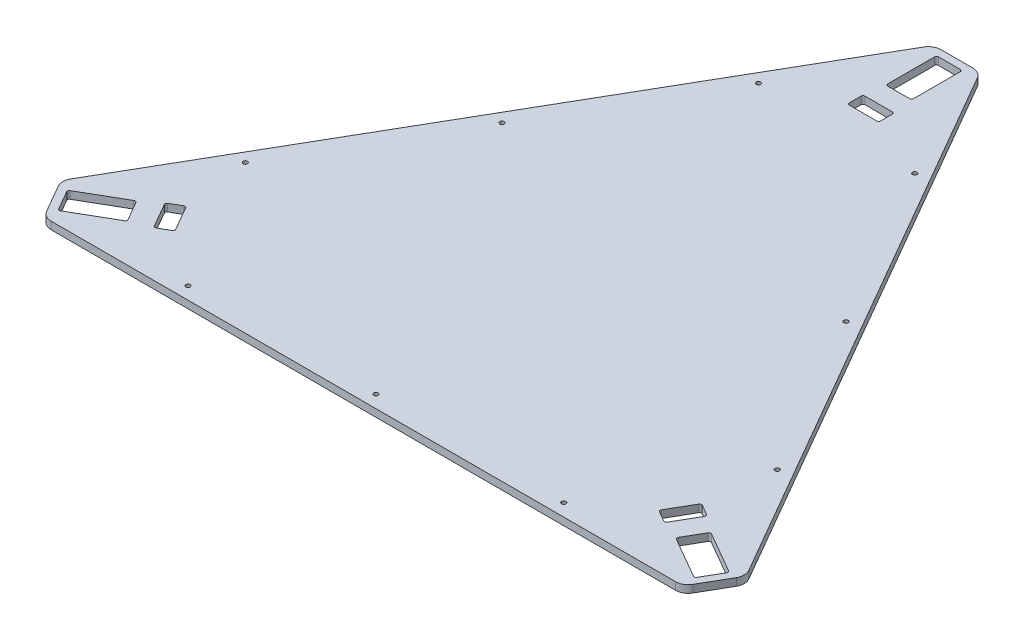
SolidWorks part; units mm, degrees
material "ABS"
ref_plane "Спереди" through (0, 0, 0) normal (0, 0, 1) x (1, 0, 0)
ref_plane "Сверху" through (0, 0, 0) normal (0, 1, 0) x (1, 0, 0)
ref_plane "Справа" through (0, 0, 0) normal (1, 0, 0) x (0, 0, -1)
sketch "Эскиз1" plane through (0, 0, 0) normal (0, 1, 0) x (1, 0, 0)
  line L17 (273.664, -136.638) -> (18.5, 305.319)
  line L18 (18.5, 305.319) -> (-18.5, 305.319)
  line L19 (-18.5, 305.319) -> (-273.664, -136.638)
  line L29 (219.0188, -138.2863) -> (254.0929, -158.5363)
  line L30 (-10.25, 299.319) -> (10.25, 299.319)
  line L31 (-273.664, -136.638) -> (-255.164, -168.681)
  line L32 (-255.164, -168.681) -> (255.164, -168.681)
  line L33 (255.164, -168.681) -> (273.664, -136.638)
  line L34 (-264.414, -152.6595) -> (0, 0) construction
  line L35 (0, 0) -> (146.082, 84.3405) construction
  line L36 (264.414, -152.6595) -> (0, 0) construction
  line L37 (0, 0) -> (-146.082, 84.3405) construction
  line L38 (0, 305.319) -> (0, 0) construction
  line L39 (0, 0) -> (0, -168.681) construction
  line L40 (-10.25, 299.319) -> (-10.25, 258.819)
  line L41 (-10.25, 258.819) -> (10.25, 258.819)
  line L42 (10.25, 299.319) -> (10.25, 258.819)
  line L43 (-10.25, 299.319) -> (10.25, 258.819) construction
  line L44 (-10.25, 258.819) -> (10.25, 299.319) construction
  line L45 (219.0188, -138.2863) -> (229.2688, -120.5327)
  line L46 (254.0929, -158.5363) -> (264.3429, -140.7827)
  line L47 (229.2688, -120.5327) -> (264.3429, -140.7827)
  line L48 (219.0188, -138.2863) -> (264.3429, -140.7827) construction
  line L49 (254.0929, -158.5363) -> (229.2688, -120.5327) construction
  line L50 (-229.2688, -120.5327) -> (-264.3429, -140.7827)
  line L51 (-229.2688, -120.5327) -> (-219.0188, -138.2863)
  line L52 (-264.3429, -140.7827) -> (-254.0929, -158.5363)
  line L53 (-219.0188, -138.2863) -> (-254.0929, -158.5363)
  line L54 (-229.2688, -120.5327) -> (-254.0929, -158.5363) construction
  line L55 (-264.3429, -140.7827) -> (-219.0188, -138.2863) construction
  line L56 (216.5374, -110.5842) -> (204.0374, -132.2348)
  line L57 (-12.5, 242.819) -> (12.5, 242.819)
  line L58 (-12.5, 242.819) -> (-12.5, 230.319)
  line L59 (-12.5, 230.319) -> (12.5, 230.319)
  line L60 (12.5, 242.819) -> (12.5, 230.319)
  line L61 (-12.5, 242.819) -> (12.5, 230.319) construction
  line L62 (-12.5, 230.319) -> (12.5, 242.819) construction
  line L63 (216.5374, -110.5842) -> (193.2121, -125.9848) construction
  line L64 (216.5374, -110.5842) -> (205.7121, -104.3342)
  line L65 (205.7121, -104.3342) -> (204.0374, -132.2348) construction
  line L66 (205.7121, -104.3342) -> (193.2121, -125.9848)
  line L67 (204.0374, -132.2348) -> (193.2121, -125.9848)
  line L68 (-204.0374, -132.2348) -> (-216.5374, -110.5842)
  line L69 (-204.0374, -132.2348) -> (-205.7121, -104.3342) construction
  line L70 (-204.0374, -132.2348) -> (-193.2121, -125.9848)
  line L71 (-193.2121, -125.9848) -> (-216.5374, -110.5842) construction
  line L72 (-193.2121, -125.9848) -> (-205.7121, -104.3342)
  line L73 (-216.5374, -110.5842) -> (-205.7121, -104.3342)
  point P3 (0, -168.681)
  point P11 (0, 305.319)
  point P14 (0, 279.069)
  point P20 (0, 236.569)
  point P22 (241.6809, -139.5345)
  point P23 (-241.6809, -139.5345)
  point P47 (0, 0)
  point P50 (-199.4621, -115.1595)
  point P51 (199.4621, -115.1595)
  dimension "D13" = 16
  dimension "D1" = 60
  dimension "D2" = 474
  dimension "D3" = 37
  dimension "D4" = 6
  dimension "D9" = 6
  dimension "D10" = 20.5
  dimension "D11" = 40.5
  dimension "D12" = 6
  dimension "D14" = 12.5
  dimension "D15" = 25
  dimension "D16" = 3
extrude "База" add sketch "Эскиз1" along normal mid plane 6
fillet "Скругление1" radius 10 6 edges at (273.664, 0, 136.638) (255.164, 0, 168.681) (-255.164, 0, 168.681) (-273.664, 0, 136.638) (18.5, 0, -305.319) (-18.5, 0, -305.319)
fillet "Скругление2" radius 1.5 24 edges at (-254.0929, 0, 158.5363) (-219.0188, 0, 138.2863) (-229.2688, 0, 120.5327) (-264.3429, 0, 140.7827) (219.0188, 0, 138.2863) (229.2688, 0, 120.5327) (264.3429, 0, 140.7827) (254.0929, 0, 158.5363) (10.25, 0, -258.819) (-10.25, 0, -258.819) (-10.25, 0, -299.319) (10.25, 0, -299.319) (12.5, 0, -230.319) (-12.5, 0, -230.319) (-12.5, 0, -242.819) (12.5, 0, -242.819) (216.5374, 0, 110.5842) (205.7121, 0, 104.3342) (193.2121, 0, 125.9848) (204.0374, 0, 132.2348) (-204.0374, 0, 132.2348) (-193.2121, 0, 125.9848) (-216.5374, 0, 110.5842) (-205.7121, 0, 104.3342)
hole_wizard "Отверстия 3,5мм" positions "Эскиз4" profile "Эскиз5" hole size "Ø3.5" standard "DIN" end condition through all
sketch "Эскиз4" plane through (0, 3, 0) normal (0, 1, 0) x (1, 0, 0)
  line L0 (-212.4218, -50.5633) -> (-137.4218, 79.3405) construction
  line L1 (-137.4218, 79.3405) -> (-62.4218, 209.2443) construction
  line L4 (62.4218, 209.2443) -> (137.4218, 79.3405) construction
  line L5 (137.4218, 79.3405) -> (212.4218, -50.5633) construction
  line L8 (150, -158.681) -> (0, -158.681) construction
  line L9 (0, -158.681) -> (-150, -158.681) construction
  line L12 (0, -158.681) -> (137.4218, 79.3405) construction
  line L13 (137.4218, 79.3405) -> (-137.4218, 79.3405) construction
  line L14 (-137.4218, 79.3405) -> (0, -158.681) construction
  line L17 (-249.3905, -168.681) -> (249.3905, -168.681) construction
  line L18 (-21.3868, 300.319) -> (-270.7773, -131.638) construction
  point P0 (-137.4218, 79.3405)
  point P2 (-62.4218, 209.2443)
  point P4 (62.4218, 209.2443)
  point P6 (137.4218, 79.3405)
  point P8 (212.4218, -50.5633)
  point P10 (150, -158.681)
  point P12 (0, -158.681)
  point P14 (-150, -158.681)
  point P16 (-212.4218, -50.5633)
  dimension "D1" = 10
  dimension "D2" = 10
  dimension "D3" = 300
  dimension "D4" = 60
  dimension "D5" = 60
sketch "Эскиз5" plane through (-137.4218, 3, -79.3405) normal (1, 0, 0) x (0, 0, 1)
  line L0 (0, 0) -> (0, 6)
  line L1 (0, 6) -> (1.75, 6)
  line L2 (1.75, 6) -> (1.75, 0)
  line L5 (1.75, 0) -> (0, 0)
  line L11 (0, -6.35) -> (0, 107.95) construction
  dimension "Диаметр сквозного отверстия" = 3.5
  dimension "Глубина сквозного отверстия" = 6
